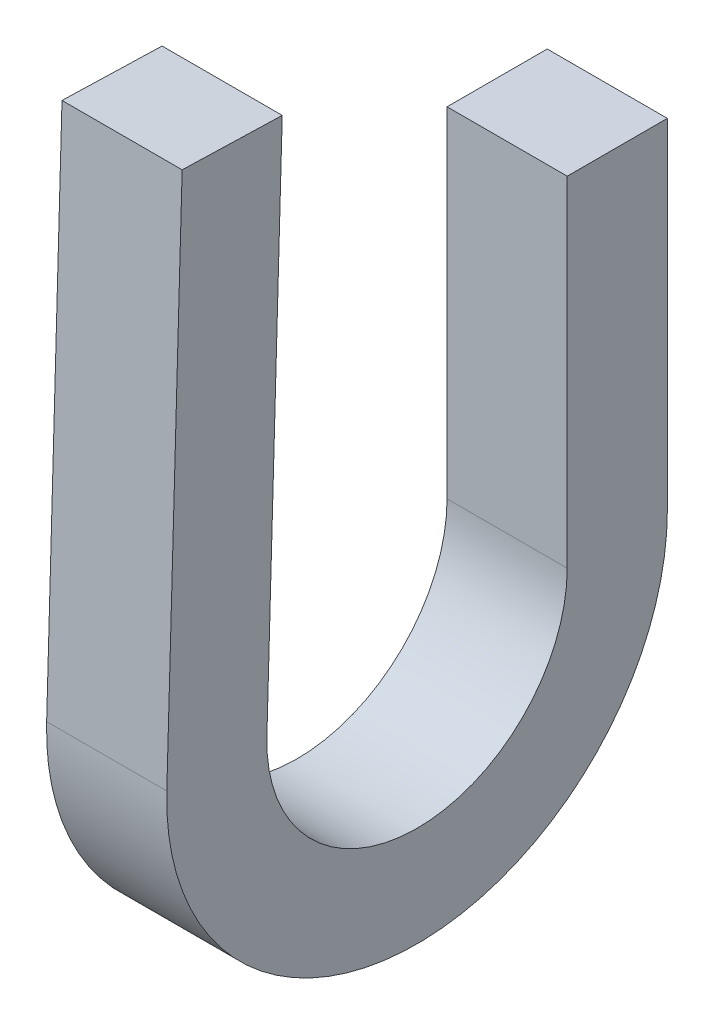
SolidWorks part; units mm, degrees
material "EPDM, dureté 60"
ref_plane "Plan de face" through (0, 0, 0) normal (0, 0, 1) x (1, 0, 0)
ref_plane "Plan de dessus" through (0, 0, 0) normal (0, 1, 0) x (1, 0, 0)
ref_plane "Plan de droite" through (0, 0, 0) normal (1, 0, 0) x (0, 0, -1)
sketch "Esquisse1" plane through (0, 0, 0) normal (0, 1, 0) x (1, 0, 0)
  line L1 (-6, -5) -> (6, -5)
  line L2 (-6, -5) -> (-6, 5)
  line L3 (-6, 5) -> (6, 5)
  line L4 (6, -5) -> (6, 5)
  point P4 (0, 5)
  point P5 (-6, 0)
  dimension "D1" = 12
  dimension "D2" = 10
sketch "Esquisse2" plane through (0, 0, 0) normal (1, 0, 0) x (0, 0, -1)
  line L0 (0, 0) -> (0, -33.9065)
  line L3 (-39.9916, -33.3276) -> (-38.458, 19.6329)
  arc A0 (0, -33.9065) -> (-39.9916, -33.3276) centre (-20, -33.9065) cw
  circle A1 centre (-38.458, 19.6329) radius 2 construction
  dimension "D1" = 150.3
  dimension "D4" = 1.659
  dimension "D2" = 20
  dimension "D3" = 38.458
sweep "Balayage1" add profiles "Esquisse1" path "Esquisse2"
